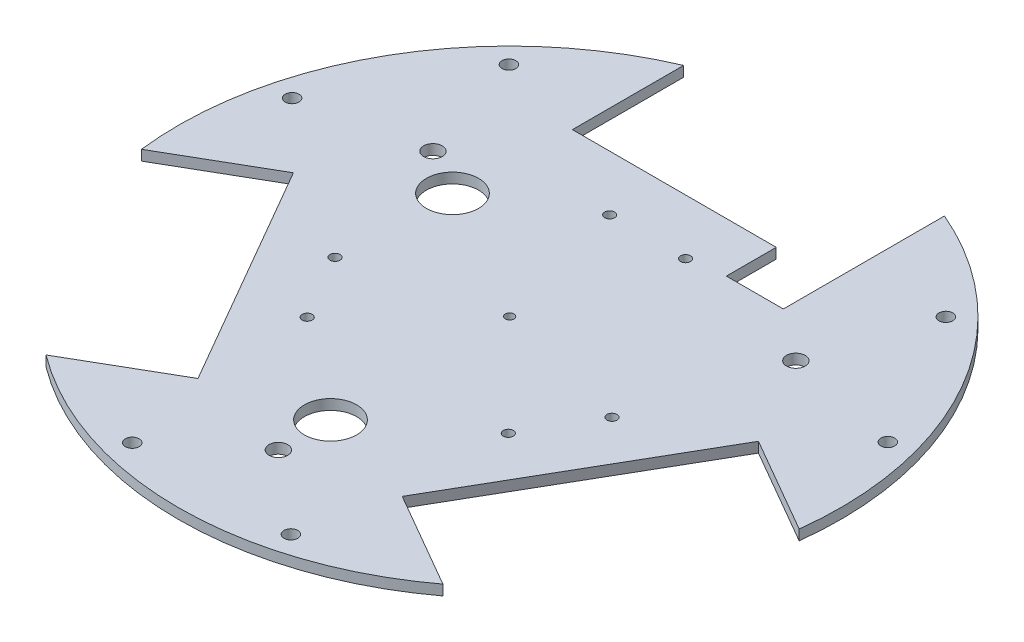
SolidWorks part; units mm, degrees
ref_plane "Front" through (0, 0, 0) normal (0, 0, 1) x (1, 0, 0)
ref_plane "Top" through (0, 0, 0) normal (0, 1, 0) x (1, 0, 0)
ref_plane "Right" through (0, 0, 0) normal (1, 0, 0) x (0, 0, -1)
sketch "Sketch1" plane through (0, 0, 0) normal (0, 1, 0) x (1, 0, 0)
  line L0 (-30, 44.45) -> (-30, 70.046)
  line L1 (-30, 44.45) -> (30, 44.45)
  line L2 (30, 44.45) -> (30, 70.046)
  line L3 (53.4948, 3.7558) -> (75.6616, -9.0422)
  line L4 (53.4948, 3.7558) -> (23.4948, -48.2058)
  line L5 (23.4948, -48.2058) -> (45.6616, -61.0038)
  line L12 (-23.4948, -48.2058) -> (-45.6616, -61.0038)
  line L15 (-23.4948, -48.2058) -> (-53.4948, 3.7558)
  line L16 (-53.4948, 3.7558) -> (-75.6616, -9.0422)
  arc A0 (75.6616, -9.0422) -> (30, 70.046) centre (0, 0) ccw
  arc A1 (-30, 70.046) -> (-75.6616, -9.0422) centre (0, 0) ccw
  arc A2 (-45.6616, -61.0038) -> (45.6616, -61.0038) centre (0, 0) ccw
  circle A3 centre (-41.7474, 24.1029) radius 2.1463
  circle A4 centre (41.7474, 24.1029) radius 2.1463
  circle A6 centre (0, -53.2058) radius 2.1463
  point P15 (-8.1441, -4.702)
  point P16 (0, 0)
  point P25 (0, 0)
  dimension "D1" = 3
  dimension "D3" = 60
  dimension "D4" = 76.2
  dimension "D5" = 60
  dimension "D6" = 60
  dimension "D8" = 25.596
extrude "Boss-Extrude1" add sketch "Sketch1" along normal blind 2.3622
sketch "Sketch2" plane through (0, 2.3622, 0) normal (0, 1, 0) x (1, 0, 0)
  circle A0 centre (18.2563, -68.58) radius 1.5875
  circle A1 centre (0, -53.2058) radius 2.1463 construction
  circle A2 centre (-18.2562, -68.58) radius 1.5875
  arc A3 (-45.6616, -61.0038) -> (45.6616, -61.0038) centre (0, 0) ccw construction
  dimension "D1" = 18.2562
  dimension "D3" = 18.2562
  dimension "D4" = 36.5125
  dimension "D2" = 68.58
extrude "Cut-Extrude1" cut sketch "Sketch2" against normal blind 10
sketch "Sketch4" plane through (0, 2.3622, 0) normal (0, 1, 0) x (1, 0, 0)
  line L0 (0, 0) -> (0, -41.2058) construction
  line L1 (0, 0) -> (-35.6852, 20.6029) construction
  circle A0 centre (0, -41.2058) radius 6
  circle A1 centre (-35.6852, 20.6029) radius 6 construction
  circle A2 centre (-31.0953, 17.9529) radius 6
  dimension "D1" = 2
  dimension "D2" = 120
extrude "Cut-Extrude3" cut sketch "Sketch4" against normal blind 10
sketch "Sketch6" plane through (0, 0, 0) normal (0, -1, 0) x (1, 0, 0)
  circle A0 centre (0, 0) radius 1
extrude "Cut-Extrude4" cut sketch "Sketch6" against normal blind 10
pattern_circular "CirPattern2" count 3 over 360 about axis through (0, 0, 0) along (0, 1, 0) of "Cut-Extrude1"
sketch "Sketch7" plane through (0, 0, 0) normal (0, -1, 0) x (1, 0, 0)
  line L0 (30, -44.45) -> (-30, -44.45) construction
  circle A0 centre (8.7312, -31.75) radius 1.1493
  circle A1 centre (-8.7312, -31.75) radius 1.1494
  dimension "D1" = 17.4625
  dimension "D2" = 12.7
extrude "Cut-Extrude5" cut sketch "Sketch7" against normal blind 2.54
pattern_circular "CirPattern3" count 3 over 360 about axis through (0, 0, 0) along (0, 1, 0) of "Cut-Extrude5"
sketch "Sketch8" plane through (0, 2.3622, 0) normal (0, 1, 0) x (1, 0, 0)
  line L1 (30, 44.45) -> (16.8935, 44.45)
  line L2 (30, 44.45) -> (30, 32.9727)
  line L3 (30, 32.9727) -> (16.8935, 32.9727)
  line L4 (16.8935, 44.45) -> (16.8935, 32.9727)
extrude "Cut-Extrude6" cut sketch "Sketch8" against normal blind 2.54
